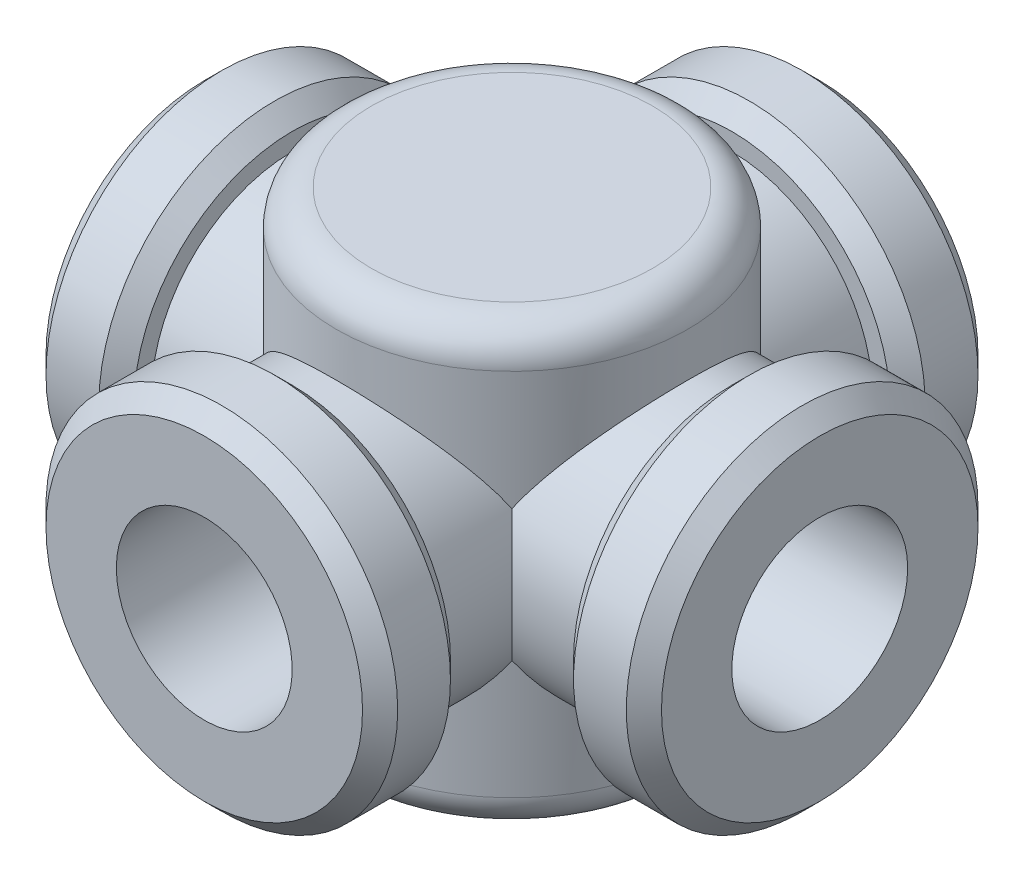
SolidWorks part; units mm, degrees
ref_plane "前视基准面" through (0, 0, 0) normal (0, 0, 1) x (1, 0, 0)
ref_plane "上视基准面" through (0, 0, 0) normal (0, 1, 0) x (1, 0, 0)
ref_plane "右视基准面" through (0, 0, 0) normal (1, 0, 0) x (0, 0, -1)
other "Configuration Table"
sketch "Sketch3" plane through (0, 0, 0) normal (0, 1, 0) x (1, 0, 0)
  circle A0 centre (0, 0) radius 5
  dimension "D1" = 10
extrude "Boss-Extrude1" add sketch "Sketch3" along normal mid plane 12.5 contours A0
sketch "Sketch4" plane through (0, 0, 0) normal (1, 0, 0) x (0, 0, -1)
  circle A0 centre (0, 0) radius 4
  dimension "D1" = 8
sketch "Sketch5" plane through (0, 0, 0) normal (0, 0, 1) x (1, 0, 0)
  circle A0 centre (0, 0) radius 4
  dimension "D1" = 8
fillet "Fillet1" radius 1 2 edges at (0, 6.25, 5) (0, -6.25, 5)
extrude "Boss-Extrude3" add sketch "Sketch5" along normal mid plane 17.5
extrude "Boss-Extrude4" add sketch "Sketch4" along normal mid plane 17.5
sketch "Sketch6" plane through (8.75, 0, 0) normal (1, 0, 0) x (0, 0, -1)
  circle A0 centre (0, 0) radius 2.5
  dimension "D1" = 5
extrude "Cut-Extrude3" cut sketch "Sketch6" against normal blind 6
sketch "Sketch7" plane through (0, 0, -8.75) normal (0, 0, -1) x (-1, 0, 0)
  circle A0 centre (0, 0) radius 2.5
  dimension "D1" = 5
extrude "Cut-Extrude4" cut sketch "Sketch7" against normal blind 6
sketch "Sketch8" plane through (-8.75, 0, 0) normal (-1, 0, 0) x (0, 0, 1)
  circle A0 centre (0, 0) radius 5
  circle A1 centre (0, 0) radius 2.5
  dimension "D1" = 5
  dimension "D2" = 10
extrude "Boss-Extrude5" add sketch "Sketch8" against normal blind 2.5
mirror "Mirror1" about plane through (0, 0, 0) normal (1, 0, 0) of "Boss-Extrude5"
sketch "Sketch9" plane through (0, 0, -8.75) normal (0, 0, -1) x (-1, 0, 0)
  circle A0 centre (0, 0) radius 2.5
  circle A1 centre (0, 0) radius 5
  dimension "D1" = 10
  dimension "D2" = 5
extrude "Boss-Extrude6" add sketch "Sketch9" against normal blind 2.5
mirror "Mirror2" about plane through (0, 0, 0) normal (0, 0, 1) of "Boss-Extrude6"
mirror "Mirror3" about plane through (0, 0, 0) normal (1, 0, 0) of "Cut-Extrude3"
mirror "Mirror4" about plane through (0, 0, 0) normal (0, 0, 1) of "Cut-Extrude4"
chamfer "Chamfer1" distance 0.5 angle 45 8 edges at (-5, 0, 8.75) (8.75, 0, 5) (-6.25, 0, 5) (-8.75, 0, 5) (-5, 0, -6.25) (-5, 0, -8.75) (-5, 0, 6.25) (6.25, 0, 5)
